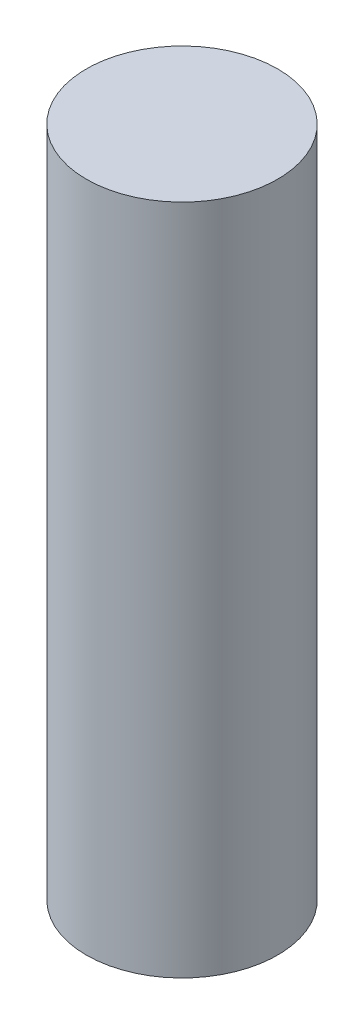
SolidWorks part; units mm, degrees
ref_plane "前视基准面" through (0, 0, 0) normal (0, 0, 1) x (1, 0, 0)
ref_plane "上视基准面" through (0, 0, 0) normal (0, 1, 0) x (1, 0, 0)
ref_plane "右视基准面" through (0, 0, 0) normal (1, 0, 0) x (0, 0, -1)
other "Configuration Table"
sketch "草图1" plane through (0, 0, 0) normal (0, 1, 0) x (1, 0, 0)
  circle A0 centre (0, 0) radius 1.85
  dimension "D1" = 3.7
extrude "凸台-拉伸1" add sketch "草图1" along normal blind 13
